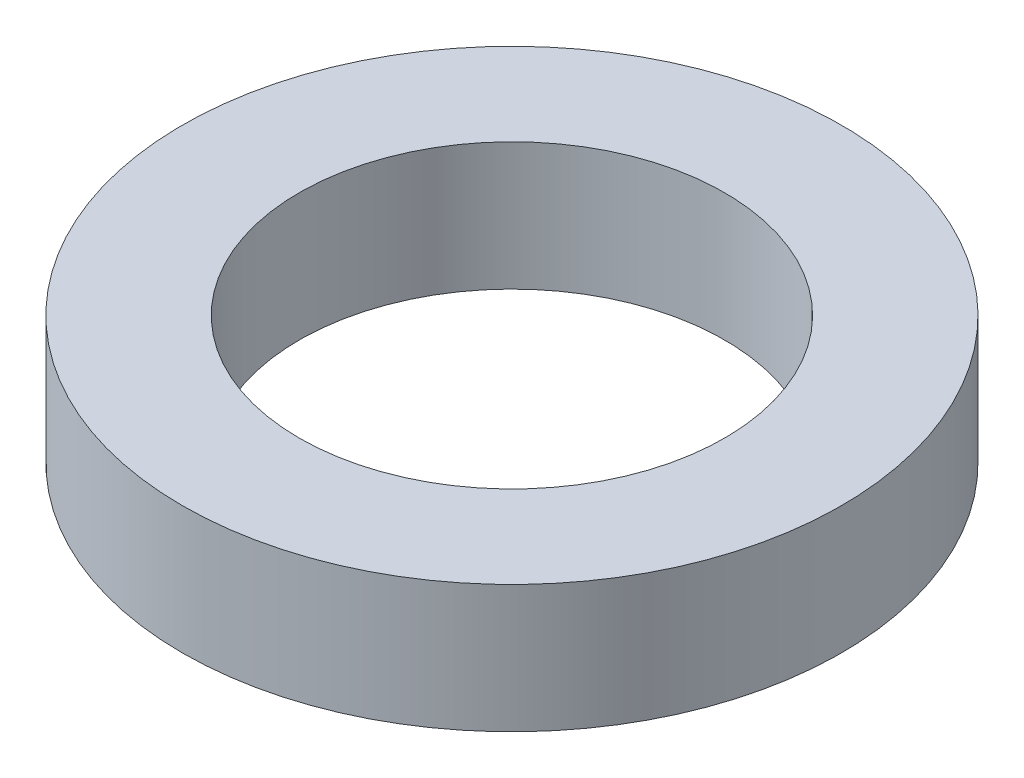
SolidWorks part; units mm, degrees
ref_plane "Front Plane" through (0, 0, 0) normal (0, 0, 1) x (1, 0, 0)
ref_plane "Top Plane" through (0, 0, 0) normal (0, 1, 0) x (1, 0, 0)
ref_plane "Right Plane" through (0, 0, 0) normal (1, 0, 0) x (0, 0, -1)
sketch "Sketch1" plane through (0, 0, 0) normal (0, 1, 0) x (1, 0, 0)
  circle A0 centre (0, 0) radius 31
  circle A1 centre (0, 0) radius 20
extrude "Boss-Extrude1" add sketch "Sketch1" along normal blind 12
